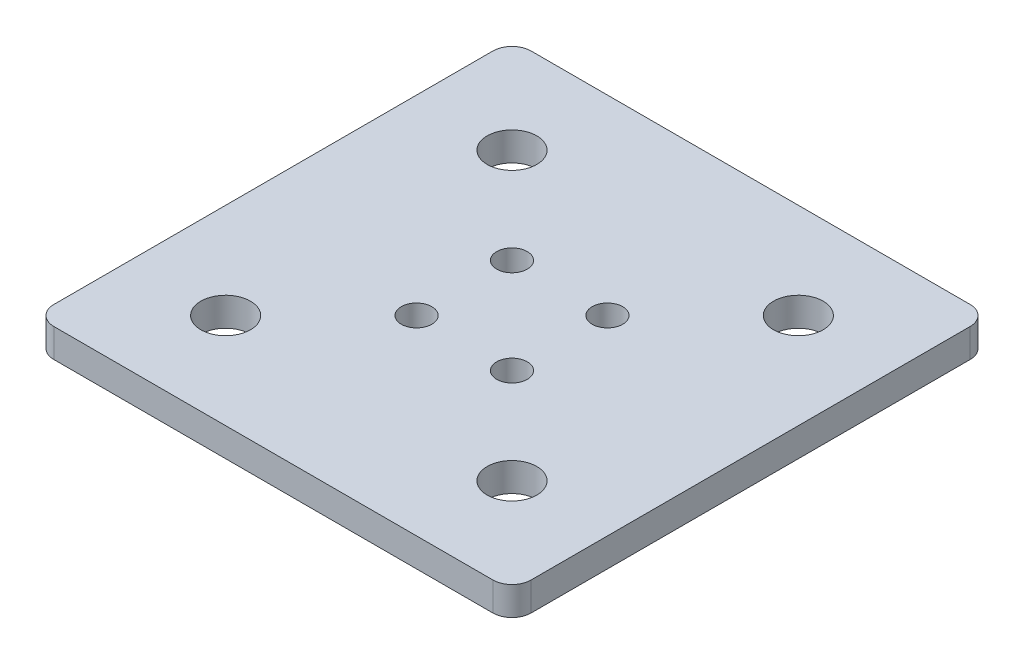
SolidWorks part; units mm, degrees
ref_plane "前视基准面" through (0, 0, 0) normal (0, 0, 1) x (1, 0, 0)
ref_plane "上视基准面" through (0, 0, 0) normal (0, 1, 0) x (1, 0, 0)
ref_plane "右视基准面" through (0, 0, 0) normal (1, 0, 0) x (0, 0, -1)
other "Configuration Table"
sketch "草图1" plane through (0, 0, 0) normal (0, 1, 0) x (1, 0, 0)
  line L0 (0, 37.2865) -> (0, -14.4922) construction
  line L1 (-25, -25) -> (25, -25)
  line L2 (-25, -25) -> (-25, 25)
  line L3 (-25, 25) -> (25, 25)
  line L4 (25, -25) -> (25, 25)
  line L5 (-25, -25) -> (25, 25) construction
  line L6 (-25, 25) -> (25, -25) construction
  line L7 (0, 0) -> (-37.1682, 0) construction
  circle A0 centre (-15, 15) radius 2.6
  circle A1 centre (-15, -15) radius 2.6
  circle A2 centre (15, -15) radius 2.6
  circle A3 centre (15, 15) radius 2.6
  circle A4 centre (-5, 5) radius 1.6
  circle A5 centre (-5, -5) radius 1.6
  circle A6 centre (5, -5) radius 1.6
  circle A7 centre (5, 5) radius 1.6
  point P0 (0, 0)
  dimension "D3" = 5.2
  dimension "D6" = 3.2
  dimension "D1" = 50
  dimension "D2" = 50
  dimension "D4" = 30
  dimension "D5" = 30
  dimension "D7" = 10
  dimension "D8" = 10
extrude "凸台-拉伸1" add sketch "草图1" along normal blind 3
fillet "圆角1" radius 2 4 edges at (-25, 1.5, 25) (25, 1.5, 25) (25, 1.5, -25) (-25, 1.5, -25)
